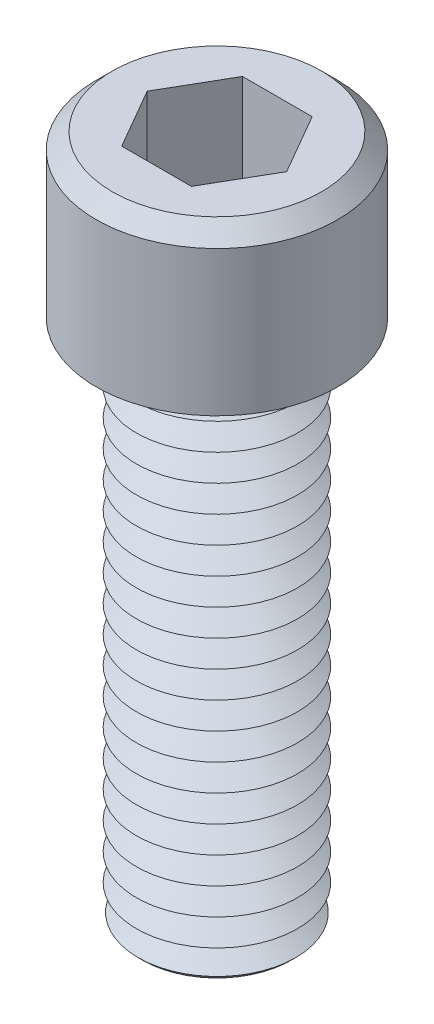
SolidWorks part; units mm, degrees
ref_plane "Front" through (0, 0, 0) normal (0, 0, 1) x (1, 0, 0)
ref_plane "Top" through (0, 0, 0) normal (0, 1, 0) x (1, 0, 0)
ref_plane "Right" through (0, 0, 0) normal (1, 0, 0) x (0, 0, -1)
ref_axis "Axis1" through (0, -50, 0) along (0, 1, 0)
sketch "Sketch ( driver )" plane through (0, 0, 0) normal (0, 0, 1) x (1, 0, 0)
  line L0 (0, 4.826) -> (3.1369, 4.826)
  line L1 (3.6195, 4.3434) -> (3.1369, 4.826)
  line L2 (3.6195, 4.3434) -> (3.6195, 0)
  line L3 (3.6195, 0) -> (2.413, 0)
  line L4 (2.413, 0) -> (2.413, -15.3924)
  line L5 (2.413, -15.3924) -> (1.9304, -15.875)
  line L6 (1.9304, -15.875) -> (0, -15.875)
  line L7 (0, -15.875) -> (0, 4.826)
  line L8 (0, 4.3688) -> (0, 4.826) construction
  line L9 (2.413, 3.8312) -> (2.413, 3.0268) construction
  line L10 (2.413, 3.0268) -> (1.7164, 3.429) construction
  line L11 (1.7164, 3.429) -> (2.413, 3.8312) construction
  circle A0 centre (0, 4.826) radius 1.8097 construction
  point P2 (0, 1.4478)
  point P12 (1.8097, 4.826)
  dimension "D4" = 3.3782
  dimension "D5" = 3.6195
  dimension "D1" = 0.4826
  dimension "Pitch" = 0.8043
  dimension "D2" = 45
  dimension "D3" = 45
  dimension "Diam" = 4.826
  dimension "Head Dia" = 7.239
  dimension "Thick" = 4.826
  dimension "Length" = 15.875
  dimension "End Chamfer" = 0.4826
  dimension "Threaded" = 19.304
sketch "Sketch3" plane through (0, 0, 0) normal (0, 0, 1) x (1, 0, 0)
  line L8 (0, 1.4478) -> (0, -15.875)
  line L9 (0, -15.875) -> (1.9304, -15.875)
  line L10 (1.9304, -15.875) -> (2.413, -15.3924)
  line L11 (2.413, -15.3924) -> (2.413, 1.4478)
  line L12 (2.413, 1.4478) -> (0, 1.4478)
revolve "Shank Revolve ( driven )" add sketch "Sketch3" angle 360 about axis through (0, -50, 0) along (0, 1, 0)
sketch "Sketch4" plane through (0, 0, 0) normal (0, 0, 1) x (1, 0, 0)
  line L0 (1.7164, 3.429) -> (2.413, 3.8312)
  line L1 (2.413, 3.8312) -> (3.2173, 3.8312)
  line L2 (3.2173, 3.8312) -> (3.2173, -17.8858)
  line L3 (1.7164, 3.429) -> (2.413, 3.0268)
  line L4 (2.413, 3.0268) -> (1.7164, 2.6247)
  line L5 (1.7164, 2.6247) -> (2.413, 2.2225)
  line L6 (2.413, 0) -> (2.413, -15.3924) construction
  line L7 (2.413, 2.2225) -> (1.7164, 1.8203)
  line L8 (1.7164, 1.8203) -> (2.413, 1.4182)
  line L9 (2.413, 1.4182) -> (1.7164, 1.016)
  line L10 (1.7164, 1.016) -> (2.413, 0.6138)
  line L11 (2.413, 0.6138) -> (1.7164, 0.2117)
  line L12 (1.7164, 0.2117) -> (2.413, -0.1905)
  line L13 (2.413, -0.1905) -> (1.7164, -0.5927)
  line L14 (1.7164, -0.5927) -> (2.413, -0.9948)
  line L15 (2.413, -0.9948) -> (1.7164, -1.397)
  line L16 (1.7164, -1.397) -> (2.413, -1.7992)
  line L17 (2.413, -1.7992) -> (1.7164, -2.2013)
  line L18 (1.7164, -2.2013) -> (2.413, -2.6035)
  line L19 (2.413, -2.6035) -> (1.7164, -3.0057)
  line L20 (1.7164, -3.0057) -> (2.413, -3.4078)
  line L21 (2.413, -3.4078) -> (1.7164, -3.81)
  line L22 (1.7164, -3.81) -> (2.413, -4.2122)
  line L23 (2.413, -4.2122) -> (1.7164, -4.6143)
  line L24 (1.7164, -4.6143) -> (2.413, -5.0165)
  line L25 (2.413, -5.0165) -> (1.7164, -5.4187)
  line L26 (1.7164, -5.4187) -> (2.413, -5.8208)
  line L27 (2.413, -5.8208) -> (1.7164, -6.223)
  line L28 (1.7164, -6.223) -> (2.413, -6.6252)
  line L29 (2.413, -6.6252) -> (1.7164, -7.0273)
  line L30 (1.7164, -7.0273) -> (2.413, -7.4295)
  line L31 (2.413, -7.4295) -> (1.7164, -7.8317)
  line L32 (1.7164, -7.8317) -> (2.413, -8.2338)
  line L33 (2.413, -8.2338) -> (1.7164, -8.636)
  line L34 (1.7164, -8.636) -> (2.413, -9.0382)
  line L35 (2.413, -9.0382) -> (1.7164, -9.4403)
  line L36 (1.7164, -9.4403) -> (2.413, -9.8425)
  line L37 (2.413, -9.8425) -> (1.7164, -10.2447)
  line L38 (1.7164, -10.2447) -> (2.413, -10.6468)
  line L39 (2.413, -17.8858) -> (3.2173, -17.8858)
  line L40 (2.413, -10.6468) -> (1.7164, -11.049)
  line L41 (1.7164, -11.049) -> (2.413, -11.4512)
  line L42 (2.413, -11.4512) -> (1.7164, -11.8533)
  line L43 (1.7164, -11.8533) -> (2.413, -12.2555)
  line L44 (2.413, -12.2555) -> (1.7164, -12.6577)
  line L45 (1.7164, -12.6577) -> (2.413, -13.0598)
  line L46 (2.413, -13.0598) -> (1.7164, -13.462)
  line L47 (1.7164, -13.462) -> (2.413, -13.8642)
  line L48 (2.413, -13.8642) -> (1.7164, -14.2663)
  line L49 (1.7164, -14.2663) -> (2.413, -14.6685)
  line L50 (2.413, -14.6685) -> (1.7164, -15.0707)
  line L51 (1.7164, -15.0707) -> (2.413, -15.4728)
  line L52 (2.413, -15.4728) -> (1.7164, -15.875)
  line L53 (1.7164, -15.875) -> (2.413, -16.2772)
  line L54 (2.413, -16.2772) -> (1.7164, -16.6793)
  line L55 (1.7164, -16.6793) -> (2.413, -17.0815)
  line L56 (2.413, -17.0815) -> (1.7164, -17.4837)
  line L57 (1.7164, -17.4837) -> (2.413, -17.8858)
revolve "Thread Revolve Cut ( driven )" cut sketch "Sketch4" angle 360 about axis through (0, -50, 0) along (0, 1, 0)
sketch "Sketch5" plane through (0, 0, 0) normal (0, 0, 1) x (1, 0, 0)
  line L0 (0, 4.826) -> (0, 0)
  line L1 (0, 0) -> (3.6195, 0)
  line L2 (3.6195, 0) -> (3.6195, 4.3434)
  line L3 (3.6195, 4.3434) -> (3.1369, 4.826)
  line L4 (3.1369, 4.826) -> (0, 4.826)
revolve "Head Revolve ( driven )" add sketch "Sketch5" angle 360 about axis through (0, -50, 0) along (0, 1, 0)
sketch "Sketch2" plane through (0, 4.826, 0) normal (0, 1, 0) x (-1, 0, 0)
  line L1 (-2.0897, 0) -> (-1.0449, -1.8097)
  line L2 (-1.0449, -1.8097) -> (1.0449, -1.8097)
  line L3 (1.0449, -1.8097) -> (2.0897, 0)
  line L4 (2.0897, 0) -> (1.0449, 1.8097)
  line L5 (1.0449, 1.8097) -> (-1.0449, 1.8098)
  line L6 (-1.0449, 1.8098) -> (-2.0897, 0)
  circle A0 centre (0, 0) radius 1.8097 construction
extrude "Hex Cut ( driven )" cut sketch "Sketch2" against normal up to vertex (3.3782 mm away) up to point (0, 1.4478, 0)
equation "\"Thick@Sketch ( driver )\" = \"Diam@Sketch ( driver )\""
equation "\"D1@Sketch ( driver )\" = .1 * \"Diam@Sketch ( driver )\""
equation "\"Pitch@Sketch ( driver )\" =  \"Diam@Sketch ( driver )\"/6"
equation "\"D4@Sketch ( driver )\" = .7*\"Diam@Sketch ( driver )\""
equation "\"End Chamfer@Sketch ( driver )\" = .1*\"Diam@Sketch ( driver )\""
equation "\"D5@Sketch ( driver )\" = .75 * \"Diam@Sketch ( driver )\""
equation "\"Threaded@Sketch ( driver )\" = 4*\"Diam@Sketch ( driver )\""
equation "\"Head Dia@Sketch ( driver )\" = 1.5 * \"Diam@Sketch ( driver )\""
